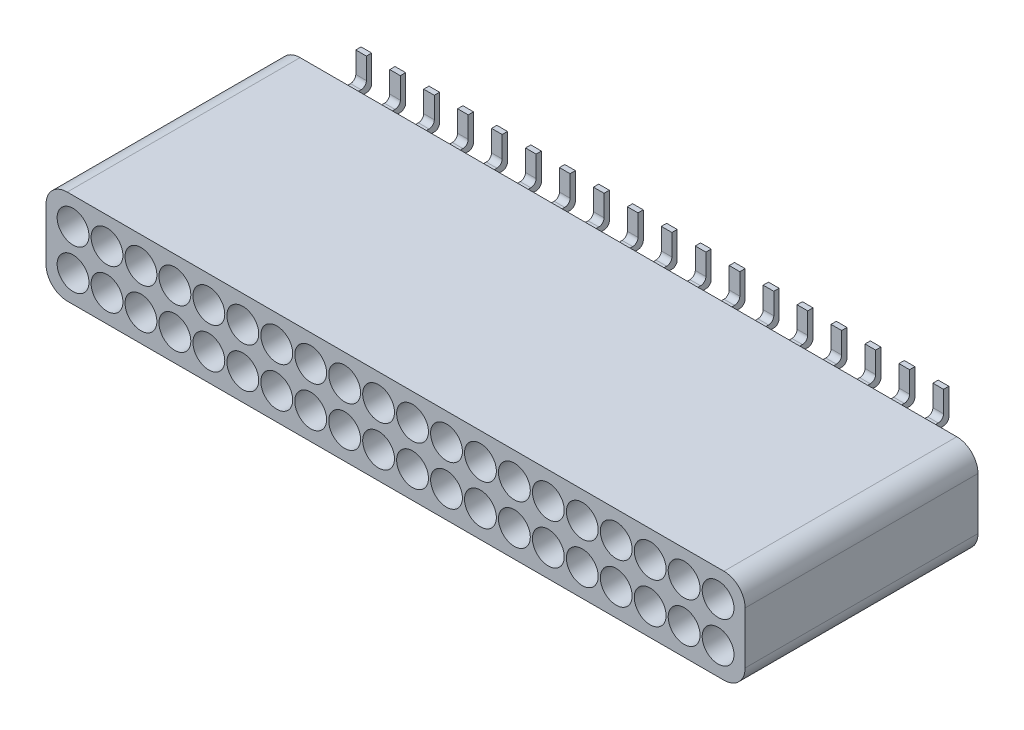
SolidWorks part; units mm, degrees
ref_plane "Front Plane" through (0, 0, 0) normal (0, 0, 1) x (1, 0, 0)
ref_plane "Top Plane" through (0, 0, 0) normal (0, 1, 0) x (1, 0, 0)
ref_plane "Right Plane" through (0, 0, 0) normal (1, 0, 0) x (0, 0, -1)
sketch "Sketch1" plane through (0, 0, 0) normal (0, 0, 1) x (1, 0, 0)
  line L5 (6.59, 0.89) -> (-6.59, 0.89)
  line L6 (6.59, 0.89) -> (6.59, -0.89)
  line L7 (6.59, -0.89) -> (-6.59, -0.89)
  line L8 (-6.59, 0.89) -> (-6.59, -0.89)
  line L9 (6.59, 0.89) -> (-6.59, -0.89) construction
  line L10 (6.59, -0.89) -> (-6.59, 0.89) construction
  point P0 (0, 0)
  dimension "D1" = 1.78
  dimension "D2" = 13.18
extrude "Boss-Extrude1" add sketch "Sketch1" along normal blind 4.39
ref_plane "Plane1" through (5.54, 0, 0) normal (1, 0, 0) x (0, 0, -1)
sketch "Sketch12" plane through (5.54, 0, 0) normal (1, 0, 0) x (0, 0, -1)
  line L0 (0, 0.54) -> (0.4, 0.54)
  line L1 (0.5, 0.64) -> (0.5, 1.14)
  line L2 (0.5, 1.14) -> (0.4, 1.14)
  line L3 (0.4, 1.14) -> (0.4, 0.74)
  line L4 (0.3, 0.64) -> (0, 0.64)
  line L5 (0, 0.64) -> (0, 0.54)
  line L6 (-4.39, 0.89) -> (0, 0.89) construction
  arc A0 (0.4, 0.54) -> (0.5, 0.64) centre (0.4, 0.64) ccw
  arc A1 (0.4, 0.74) -> (0.3, 0.64) centre (0.3, 0.74) cw
  point P2 (0, 0)
  point P11 (0.5, 0.54)
  point P14 (0.4, 0.64)
  dimension "D6" = 0.1
  dimension "D1" = 0.35
  dimension "D2" = 0.1
  dimension "D3" = 0.4
  dimension "D4" = 0.6
  dimension "D5" = 0.1
extrude "Boss-Extrude3" add sketch "Sketch12" against normal blind 0.2
pattern_linear "LPattern2" count 18 spacing 0.64 along (-1, 0, 0) of "Boss-Extrude3"
mirror "Mirror1" about plane through (0, 0, 0) normal (0, 1, 0) of "LPattern2", "Boss-Extrude3"
sketch "Sketch3" plane through (0, 0, 4.39) normal (0, 0, 1) x (1, 0, 0)
  line L2 (6.59, -0.89) -> (6.59, 0.89) construction
  circle A1 centre (6.08, -0.38) radius 0.3
  point P7 (6.59, 0)
  point P11 (6.08, -0.115)
  dimension "D1" = 0.6
  dimension "D3" = 0.38
  dimension "D2" = 0.51
extrude "Cut-Extrude1" cut sketch "Sketch3" against normal blind 3 contours A1
pattern_linear "LPattern1" count 20 spacing 0.64 along (-1, 0, 0) count 2 spacing 0.76 along (0, 1, 0) of "Cut-Extrude1"
fillet "Fillet1" radius 0.4 4 edges at (6.59, 0.89, 2.195) (6.59, -0.89, 2.195) (-6.59, -0.89, 2.195) (-6.59, 0.89, 2.195)
move or copy body "Body-Move/Copy1" bodies to move or copy 104 copy no translate (0, 0, 0.5)
